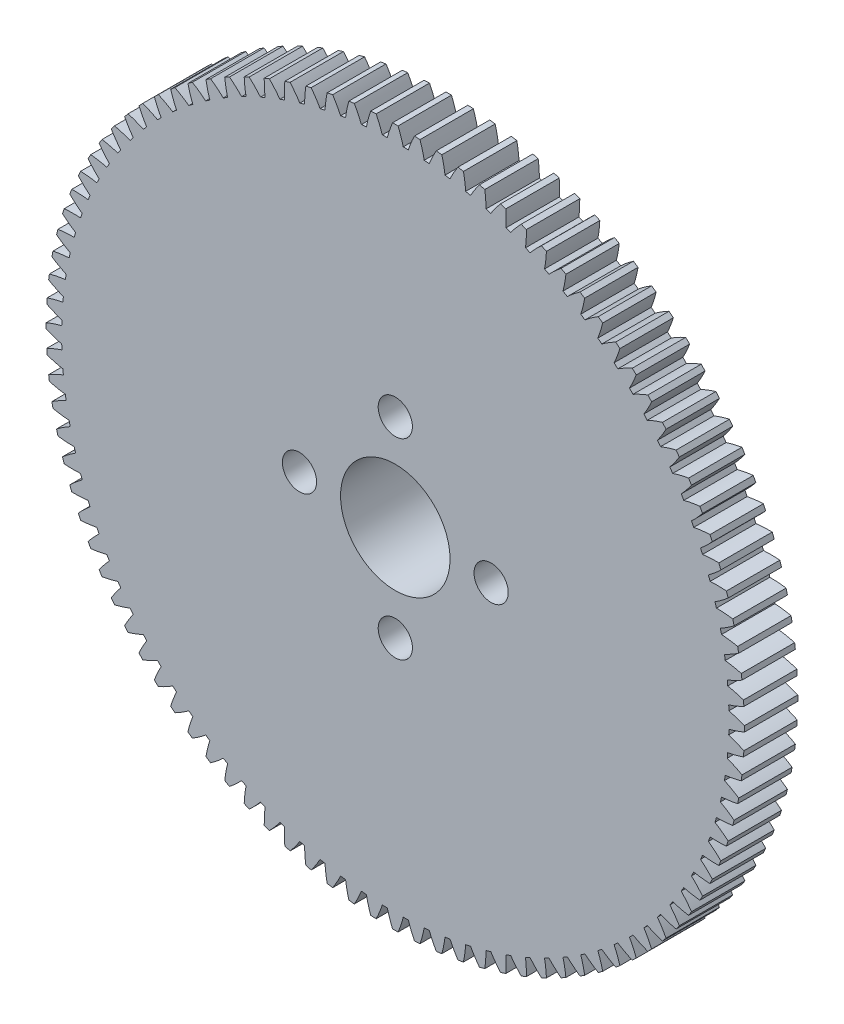
SolidWorks part; units mm, degrees
material "ABS"
ref_plane "Front Plane" through (0, 0, 0) normal (0, 0, 1) x (1, 0, 0)
ref_plane "Top Plane" through (0, 0, 0) normal (0, 1, 0) x (1, 0, 0)
ref_plane "Right Plane" through (0, 0, 0) normal (1, 0, 0) x (0, 0, -1)
ref_plane "Plane1" through (0, 0, 4.1) normal (0, 0, 1) x (1, 0, 0)
sketch "Sketch1" plane through (0, 0, 4.1) normal (0, 0, 1) x (1, 0, 0)
  line L0 (25.4992, -0.2018) -> (25.4992, 0.2018)
  line L1 (25.4616, 1.3997) -> (25.4362, 1.8025)
  line L2 (25.3234, 2.9957) -> (25.2728, 3.3961)
  line L3 (25.0854, 4.5799) -> (25.0097, 4.9763)
  line L4 (24.7483, 6.1459) -> (24.6479, 6.5369)
  line L5 (24.3135, 7.6878) -> (24.1888, 8.0716)
  line L6 (23.7828, 9.1993) -> (23.6343, 9.5745)
  line L7 (23.1583, 10.6744) -> (22.9864, 11.0396)
  line L8 (22.4423, 12.1075) -> (22.2479, 12.4612)
  line L9 (21.6378, 13.4928) -> (21.4216, 13.8335)
  line L10 (20.7479, 14.8248) -> (20.5107, 15.1513)
  line L11 (19.7761, 16.0983) -> (19.5188, 16.4093)
  line L12 (18.7263, 17.3083) -> (18.45, 17.6025)
  line L13 (17.6025, 18.45) -> (17.3083, 18.7263)
  line L14 (16.4093, 19.5188) -> (16.0983, 19.7761)
  line L15 (15.1513, 20.5107) -> (14.8248, 20.7479)
  line L16 (13.8335, 21.4216) -> (13.4928, 21.6378)
  line L17 (12.4612, 22.2479) -> (12.1075, 22.4423)
  line L18 (11.0396, 22.9864) -> (10.6744, 23.1583)
  line L19 (9.5745, 23.6343) -> (9.1993, 23.7828)
  line L20 (8.0716, 24.1888) -> (7.6878, 24.3135)
  line L21 (6.5369, 24.6479) -> (6.1459, 24.7483)
  line L22 (4.9763, 25.0097) -> (4.5799, 25.0854)
  line L23 (3.3961, 25.2728) -> (2.9957, 25.3234)
  line L24 (1.8025, 25.4362) -> (1.3997, 25.4616)
  line L25 (0.2018, 25.4992) -> (-0.2018, 25.4992)
  line L26 (-1.3997, 25.4616) -> (-1.8025, 25.4362)
  line L27 (-2.9957, 25.3234) -> (-3.3961, 25.2728)
  line L28 (-4.5799, 25.0854) -> (-4.9763, 25.0097)
  line L29 (-6.1459, 24.7483) -> (-6.5369, 24.6479)
  line L30 (-7.6878, 24.3135) -> (-8.0716, 24.1888)
  line L31 (-9.1993, 23.7828) -> (-9.5745, 23.6343)
  line L32 (-10.6744, 23.1583) -> (-11.0396, 22.9864)
  line L33 (-12.1075, 22.4423) -> (-12.4612, 22.2479)
  line L34 (-13.4928, 21.6378) -> (-13.8335, 21.4216)
  line L35 (-14.8248, 20.7479) -> (-15.1513, 20.5107)
  line L36 (-16.0983, 19.7761) -> (-16.4093, 19.5188)
  line L37 (-17.3083, 18.7263) -> (-17.6025, 18.45)
  line L38 (-18.45, 17.6025) -> (-18.7263, 17.3083)
  line L39 (-19.5188, 16.4093) -> (-19.7761, 16.0983)
  line L40 (-20.5107, 15.1513) -> (-20.7479, 14.8248)
  line L41 (-21.4216, 13.8335) -> (-21.6378, 13.4928)
  line L42 (-22.2479, 12.4612) -> (-22.4423, 12.1075)
  line L43 (-22.9864, 11.0396) -> (-23.1583, 10.6744)
  line L44 (-23.6343, 9.5745) -> (-23.7828, 9.1993)
  line L45 (-24.1888, 8.0716) -> (-24.3135, 7.6878)
  line L46 (-24.6479, 6.5369) -> (-24.7483, 6.1459)
  line L47 (-25.0097, 4.9763) -> (-25.0854, 4.5799)
  line L48 (-25.2728, 3.3961) -> (-25.3234, 2.9957)
  line L49 (-25.4362, 1.8025) -> (-25.4616, 1.3997)
  line L50 (-25.4992, 0.2018) -> (-25.4992, -0.2018)
  line L51 (-25.4616, -1.3997) -> (-25.4362, -1.8025)
  line L52 (-25.3234, -2.9957) -> (-25.2728, -3.3961)
  line L53 (-25.0854, -4.5799) -> (-25.0097, -4.9763)
  line L54 (-24.7483, -6.1459) -> (-24.6479, -6.5369)
  line L55 (-24.3135, -7.6878) -> (-24.1888, -8.0716)
  line L56 (-23.7828, -9.1993) -> (-23.6343, -9.5745)
  line L57 (-23.1583, -10.6744) -> (-22.9864, -11.0396)
  line L58 (-22.4423, -12.1075) -> (-22.2479, -12.4612)
  line L59 (-21.6378, -13.4928) -> (-21.4216, -13.8335)
  line L60 (-20.7479, -14.8248) -> (-20.5107, -15.1513)
  line L61 (-19.7761, -16.0983) -> (-19.5188, -16.4093)
  line L62 (-18.7263, -17.3083) -> (-18.45, -17.6025)
  line L63 (-17.6025, -18.45) -> (-17.3083, -18.7263)
  line L64 (-16.4093, -19.5188) -> (-16.0983, -19.7761)
  line L65 (-15.1513, -20.5107) -> (-14.8248, -20.7479)
  line L66 (-13.8335, -21.4216) -> (-13.4928, -21.6378)
  line L67 (-12.4612, -22.2479) -> (-12.1075, -22.4423)
  line L68 (-11.0396, -22.9864) -> (-10.6744, -23.1583)
  line L69 (-9.5745, -23.6343) -> (-9.1993, -23.7828)
  line L70 (-8.0716, -24.1888) -> (-7.6878, -24.3135)
  line L71 (-6.5369, -24.6479) -> (-6.1459, -24.7483)
  line L72 (-4.9763, -25.0097) -> (-4.5799, -25.0854)
  line L73 (-3.3961, -25.2728) -> (-2.9957, -25.3234)
  line L74 (-1.8025, -25.4362) -> (-1.3997, -25.4616)
  line L75 (-0.2018, -25.4992) -> (0.2018, -25.4992)
  line L76 (1.3997, -25.4616) -> (1.8025, -25.4362)
  line L77 (2.9957, -25.3234) -> (3.3961, -25.2728)
  line L78 (4.5799, -25.0854) -> (4.9763, -25.0097)
  line L79 (6.1459, -24.7483) -> (6.5369, -24.6479)
  line L80 (7.6878, -24.3135) -> (8.0716, -24.1888)
  line L81 (9.1993, -23.7828) -> (9.5745, -23.6343)
  line L82 (10.6744, -23.1583) -> (11.0396, -22.9864)
  line L83 (12.1075, -22.4423) -> (12.4612, -22.2479)
  line L84 (13.4928, -21.6378) -> (13.8335, -21.4216)
  line L85 (14.8248, -20.7479) -> (15.1513, -20.5107)
  line L86 (16.0983, -19.7761) -> (16.4093, -19.5188)
  line L87 (17.3083, -18.7263) -> (17.6025, -18.45)
  line L88 (18.45, -17.6025) -> (18.7263, -17.3083)
  line L89 (19.5188, -16.4093) -> (19.7761, -16.0983)
  line L90 (20.5107, -15.1513) -> (20.7479, -14.8248)
  line L91 (21.4216, -13.8335) -> (21.6378, -13.4928)
  line L92 (22.2479, -12.4612) -> (22.4423, -12.1075)
  line L93 (22.9864, -11.0396) -> (23.1583, -10.6744)
  line L94 (23.6343, -9.5745) -> (23.7828, -9.1993)
  line L95 (24.1888, -8.0716) -> (24.3135, -7.6878)
  line L96 (24.6479, -6.5369) -> (24.7483, -6.1459)
  line L97 (25.0097, -4.9763) -> (25.0854, -4.5799)
  line L98 (25.2728, -3.3961) -> (25.3234, -2.9957)
  line L99 (25.4362, -1.8025) -> (25.4616, -1.3997)
  arc A0 (24.3565, -0.9497) -> (24.3681, -0.5815) centre (0, 0) ccw
  arc A1 (24.3681, -0.5815) -> (25.4992, -0.2018) centre (22.3084, 7.4288) ccw
  arc A2 (25.4992, 0.2018) -> (24.3681, 0.5815) centre (22.3272, -7.3729) ccw
  arc A3 (24.3681, 0.5815) -> (24.3565, 0.9497) centre (0, 0) ccw
  arc A4 (24.3565, 0.9497) -> (25.4616, 1.3997) centre (21.7979, 8.8149) ccw
  arc A5 (25.4362, 1.8025) -> (24.2835, 2.1104) centre (22.7461, -5.9564) ccw
  arc A6 (24.2835, 2.1104) -> (24.2488, 2.4772) centre (0, 0) ccw
  arc A7 (24.2488, 2.4772) -> (25.3234, 2.9957) centre (21.2014, 10.1662) ccw
  arc A8 (25.2728, 3.3961) -> (24.103, 3.631) centre (23.0752, -4.5164) ccw
  arc A9 (24.103, 3.631) -> (24.0454, 3.9949) centre (0, 0) ccw
  arc A10 (24.0454, 3.9949) -> (25.0854, 4.5799) centre (20.5213, 11.4774) ccw
  arc A11 (25.0097, 4.9763) -> (23.8275, 5.1373) centre (23.3132, -3.0586) ccw
  arc A12 (23.8275, 5.1373) -> (23.7471, 5.4969) centre (0, 0) ccw
  arc A13 (23.7471, 5.4969) -> (24.7483, 6.1459) centre (19.7601, 12.7433) ccw
  arc A14 (24.6479, 6.5369) -> (23.4579, 6.6233) centre (23.4593, -1.5887) ccw
  arc A15 (23.4579, 6.6233) -> (23.3551, 6.9771) centre (0, 0) ccw
  arc A16 (23.3551, 6.9771) -> (24.3135, 7.6878) centre (18.921, 13.9589) ccw
  arc A17 (24.1888, 8.0716) -> (22.9957, 8.0832) centre (23.5128, -0.1125) ccw
  arc A18 (22.9957, 8.0832) -> (22.8709, 8.4298) centre (0, 0) ccw
  arc A19 (22.8709, 8.4298) -> (23.7828, 9.1993) centre (18.0071, 15.1194) ccw
  arc A20 (23.6343, 9.5745) -> (22.4428, 9.5112) centre (23.4734, 1.3641) ccw
  arc A21 (22.4428, 9.5112) -> (22.2965, 9.8493) centre (0, 0) ccw
  arc A22 (22.2965, 9.8493) -> (23.1583, 10.6744) centre (17.0222, 16.2202) ccw
  arc A23 (22.9864, 11.0396) -> (21.8013, 10.9016) centre (23.3415, 2.8353) ccw
  arc A24 (21.8013, 10.9016) -> (21.634, 11.2298) centre (0, 0) ccw
  arc A25 (21.634, 11.2298) -> (22.4423, 12.1075) centre (15.9702, 17.257) ccw
  arc A26 (22.2479, 12.4612) -> (21.0738, 12.249) centre (23.1174, 4.2953) ccw
  arc A27 (21.0738, 12.249) -> (20.8862, 12.5661) centre (0, 0) ccw
  arc A28 (20.8862, 12.5661) -> (21.6378, 13.4928) centre (14.8551, 18.2258) ccw
  arc A29 (21.4216, 13.8335) -> (20.263, 13.548) centre (22.8021, 5.7384) ccw
  arc A30 (20.263, 13.548) -> (20.056, 13.8527) centre (0, 0) ccw
  arc A31 (20.056, 13.8527) -> (20.7479, 14.8248) centre (13.6814, 19.1226) ccw
  arc A32 (20.5107, 15.1513) -> (19.3724, 14.7936) centre (22.3967, 7.1588) ccw
  arc A33 (19.3724, 14.7936) -> (19.1466, 15.0847) centre (0, 0) ccw
  arc A34 (19.1466, 15.0847) -> (19.7761, 16.0983) centre (12.4537, 19.9439) ccw
  arc A35 (19.5188, 16.4093) -> (18.4052, 15.9808) centre (21.903, 8.551) ccw
  arc A36 (18.4052, 15.9808) -> (18.1616, 16.2572) centre (0, 0) ccw
  arc A37 (18.1616, 16.2572) -> (18.7263, 17.3083) centre (11.1768, 20.6865) ccw
  arc A38 (18.45, 17.6025) -> (17.3655, 17.105) centre (21.3229, 9.9094) ccw
  arc A39 (17.3655, 17.105) -> (17.105, 17.3655) centre (0, 0) ccw
  arc A40 (17.105, 17.3655) -> (17.6025, 18.45) centre (9.8558, 21.3475) ccw
  arc A41 (17.3083, 18.7263) -> (16.2572, 18.1616) centre (20.6586, 11.2287) ccw
  arc A42 (16.2572, 18.1616) -> (15.9808, 18.4052) centre (0, 0) ccw
  arc A43 (15.9808, 18.4052) -> (16.4093, 19.5188) centre (8.496, 21.9242) ccw
  arc A44 (16.0983, 19.7761) -> (15.0847, 19.1466) centre (19.9128, 12.5037) ccw
  arc A45 (15.0847, 19.1466) -> (14.7936, 19.3724) centre (0, 0) ccw
  arc A46 (14.7936, 19.3724) -> (15.1513, 20.5107) centre (7.1026, 22.4144) ccw
  arc A47 (14.8248, 20.7479) -> (13.8527, 20.056) centre (19.0884, 13.7294) ccw
  arc A48 (13.8527, 20.056) -> (13.548, 20.263) centre (0, 0) ccw
  arc A49 (13.548, 20.263) -> (13.8335, 21.4216) centre (5.6811, 22.8162) ccw
  arc A50 (13.4928, 21.6378) -> (12.5661, 20.8862) centre (18.1886, 14.9009) ccw
  arc A51 (12.5661, 20.8862) -> (12.249, 21.0738) centre (0, 0) ccw
  arc A52 (12.249, 21.0738) -> (12.4612, 22.2479) centre (4.2373, 23.1279) ccw
  arc A53 (12.1075, 22.4423) -> (11.2298, 21.634) centre (17.2171, 16.0136) ccw
  arc A54 (11.2298, 21.634) -> (10.9016, 21.8013) centre (0, 0) ccw
  arc A55 (10.9016, 21.8013) -> (11.0396, 22.9864) centre (2.7767, 23.3483) ccw
  arc A56 (10.6744, 23.1583) -> (9.8493, 22.2965) centre (16.1776, 17.063) ccw
  arc A57 (9.8493, 22.2965) -> (9.5112, 22.4428) centre (0, 0) ccw
  arc A58 (9.5112, 22.4428) -> (9.5745, 23.6343) centre (1.3052, 23.4766) ccw
  arc A59 (9.1993, 23.7828) -> (8.4298, 22.8709) centre (15.0743, 18.0452) ccw
  arc A60 (8.4298, 22.8709) -> (8.0832, 22.9957) centre (0, 0) ccw
  arc A61 (8.0832, 22.9957) -> (8.0716, 24.1888) centre (-0.1715, 23.5122) ccw
  arc A62 (7.6878, 24.3135) -> (6.9771, 23.3551) centre (13.9115, 18.9561) ccw
  arc A63 (6.9771, 23.3551) -> (6.6233, 23.4579) centre (0, 0) ccw
  arc A64 (6.6233, 23.4579) -> (6.5369, 24.6479) centre (-1.6475, 23.455) ccw
  arc A65 (6.1459, 24.7483) -> (5.4969, 23.7471) centre (12.6938, 19.7922) ccw
  arc A66 (5.4969, 23.7471) -> (5.1373, 23.8275) centre (0, 0) ccw
  arc A67 (5.1373, 23.8275) -> (4.9763, 25.0097) centre (-3.117, 23.3053) ccw
  arc A68 (4.5799, 25.0854) -> (3.9949, 24.0454) centre (11.426, 20.5502) ccw
  arc A69 (3.9949, 24.0454) -> (3.631, 24.103) centre (0, 0) ccw
  arc A70 (3.631, 24.103) -> (3.3961, 25.2728) centre (-4.5742, 23.0636) ccw
  arc A71 (2.9957, 25.3234) -> (2.4772, 24.2488) centre (10.1131, 21.2271) ccw
  arc A72 (2.4772, 24.2488) -> (2.1104, 24.2835) centre (0, 0) ccw
  arc A73 (2.1104, 24.2835) -> (1.8025, 25.4362) centre (-6.0134, 22.7309) ccw
  arc A74 (1.3997, 25.4616) -> (0.9497, 24.3565) centre (8.7603, 21.8202) ccw
  arc A75 (0.9497, 24.3565) -> (0.5815, 24.3681) centre (0, 0) ccw
  arc A76 (0.5815, 24.3681) -> (0.2018, 25.4992) centre (-7.4288, 22.3084) ccw
  arc A77 (-0.2018, 25.4992) -> (-0.5815, 24.3681) centre (7.3729, 22.3272) ccw
  arc A78 (-0.5815, 24.3681) -> (-0.9497, 24.3565) centre (0, 0) ccw
  arc A79 (-0.9497, 24.3565) -> (-1.3997, 25.4616) centre (-8.8149, 21.7979) ccw
  arc A80 (-1.8025, 25.4362) -> (-2.1104, 24.2835) centre (5.9564, 22.7461) ccw
  arc A81 (-2.1104, 24.2835) -> (-2.4772, 24.2488) centre (0, 0) ccw
  arc A82 (-2.4772, 24.2488) -> (-2.9957, 25.3234) centre (-10.1662, 21.2014) ccw
  arc A83 (-3.3961, 25.2728) -> (-3.631, 24.103) centre (4.5164, 23.0752) ccw
  arc A84 (-3.631, 24.103) -> (-3.9949, 24.0454) centre (0, 0) ccw
  arc A85 (-3.9949, 24.0454) -> (-4.5799, 25.0854) centre (-11.4774, 20.5213) ccw
  arc A86 (-4.9763, 25.0097) -> (-5.1373, 23.8275) centre (3.0586, 23.3132) ccw
  arc A87 (-5.1373, 23.8275) -> (-5.4969, 23.7471) centre (0, 0) ccw
  arc A88 (-5.4969, 23.7471) -> (-6.1459, 24.7483) centre (-12.7433, 19.7601) ccw
  arc A89 (-6.5369, 24.6479) -> (-6.6233, 23.4579) centre (1.5887, 23.4593) ccw
  arc A90 (-6.6233, 23.4579) -> (-6.9771, 23.3551) centre (0, 0) ccw
  arc A91 (-6.9771, 23.3551) -> (-7.6878, 24.3135) centre (-13.9589, 18.921) ccw
  arc A92 (-8.0716, 24.1888) -> (-8.0832, 22.9957) centre (0.1125, 23.5128) ccw
  arc A93 (-8.0832, 22.9957) -> (-8.4298, 22.8709) centre (0, 0) ccw
  arc A94 (-8.4298, 22.8709) -> (-9.1993, 23.7828) centre (-15.1194, 18.0071) ccw
  arc A95 (-9.5745, 23.6343) -> (-9.5112, 22.4428) centre (-1.3641, 23.4734) ccw
  arc A96 (-9.5112, 22.4428) -> (-9.8493, 22.2965) centre (0, 0) ccw
  arc A97 (-9.8493, 22.2965) -> (-10.6744, 23.1583) centre (-16.2202, 17.0222) ccw
  arc A98 (-11.0396, 22.9864) -> (-10.9016, 21.8013) centre (-2.8353, 23.3415) ccw
  arc A99 (-10.9016, 21.8013) -> (-11.2298, 21.634) centre (0, 0) ccw
  arc A100 (-11.2298, 21.634) -> (-12.1075, 22.4423) centre (-17.257, 15.9702) ccw
  arc A101 (-12.4612, 22.2479) -> (-12.249, 21.0738) centre (-4.2953, 23.1174) ccw
  arc A102 (-12.249, 21.0738) -> (-12.5661, 20.8862) centre (0, 0) ccw
  arc A103 (-12.5661, 20.8862) -> (-13.4928, 21.6378) centre (-18.2258, 14.8551) ccw
  arc A104 (-13.8335, 21.4216) -> (-13.548, 20.263) centre (-5.7384, 22.8021) ccw
  arc A105 (-13.548, 20.263) -> (-13.8527, 20.056) centre (0, 0) ccw
  arc A106 (-13.8527, 20.056) -> (-14.8248, 20.7479) centre (-19.1226, 13.6814) ccw
  arc A107 (-15.1513, 20.5107) -> (-14.7936, 19.3724) centre (-7.1588, 22.3967) ccw
  arc A108 (-14.7936, 19.3724) -> (-15.0847, 19.1466) centre (0, 0) ccw
  arc A109 (-15.0847, 19.1466) -> (-16.0983, 19.7761) centre (-19.9439, 12.4537) ccw
  arc A110 (-16.4093, 19.5188) -> (-15.9808, 18.4052) centre (-8.551, 21.903) ccw
  arc A111 (-15.9808, 18.4052) -> (-16.2572, 18.1616) centre (0, 0) ccw
  arc A112 (-16.2572, 18.1616) -> (-17.3083, 18.7263) centre (-20.6865, 11.1768) ccw
  arc A113 (-17.6025, 18.45) -> (-17.105, 17.3655) centre (-9.9094, 21.3229) ccw
  arc A114 (-17.105, 17.3655) -> (-17.3655, 17.105) centre (0, 0) ccw
  arc A115 (-17.3655, 17.105) -> (-18.45, 17.6025) centre (-21.3475, 9.8558) ccw
  arc A116 (-18.7263, 17.3083) -> (-18.1616, 16.2572) centre (-11.2287, 20.6586) ccw
  arc A117 (-18.1616, 16.2572) -> (-18.4052, 15.9808) centre (0, 0) ccw
  arc A118 (-18.4052, 15.9808) -> (-19.5188, 16.4093) centre (-21.9242, 8.496) ccw
  arc A119 (-19.7761, 16.0983) -> (-19.1466, 15.0847) centre (-12.5037, 19.9128) ccw
  arc A120 (-19.1466, 15.0847) -> (-19.3724, 14.7936) centre (0, 0) ccw
  arc A121 (-19.3724, 14.7936) -> (-20.5107, 15.1513) centre (-22.4144, 7.1026) ccw
  arc A122 (-20.7479, 14.8248) -> (-20.056, 13.8527) centre (-13.7294, 19.0884) ccw
  arc A123 (-20.056, 13.8527) -> (-20.263, 13.548) centre (0, 0) ccw
  arc A124 (-20.263, 13.548) -> (-21.4216, 13.8335) centre (-22.8162, 5.6811) ccw
  arc A125 (-21.6378, 13.4928) -> (-20.8862, 12.5661) centre (-14.9009, 18.1886) ccw
  arc A126 (-20.8862, 12.5661) -> (-21.0738, 12.249) centre (0, 0) ccw
  arc A127 (-21.0738, 12.249) -> (-22.2479, 12.4612) centre (-23.1279, 4.2373) ccw
  arc A128 (-22.4423, 12.1075) -> (-21.634, 11.2298) centre (-16.0136, 17.2171) ccw
  arc A129 (-21.634, 11.2298) -> (-21.8013, 10.9016) centre (0, 0) ccw
  arc A130 (-21.8013, 10.9016) -> (-22.9864, 11.0396) centre (-23.3483, 2.7767) ccw
  arc A131 (-23.1583, 10.6744) -> (-22.2965, 9.8493) centre (-17.063, 16.1776) ccw
  arc A132 (-22.2965, 9.8493) -> (-22.4428, 9.5112) centre (0, 0) ccw
  arc A133 (-22.4428, 9.5112) -> (-23.6343, 9.5745) centre (-23.4766, 1.3052) ccw
  arc A134 (-23.7828, 9.1993) -> (-22.8709, 8.4298) centre (-18.0452, 15.0743) ccw
  arc A135 (-22.8709, 8.4298) -> (-22.9957, 8.0832) centre (0, 0) ccw
  arc A136 (-22.9957, 8.0832) -> (-24.1888, 8.0716) centre (-23.5122, -0.1715) ccw
  arc A137 (-24.3135, 7.6878) -> (-23.3551, 6.9771) centre (-18.9561, 13.9115) ccw
  arc A138 (-23.3551, 6.9771) -> (-23.4579, 6.6233) centre (0, 0) ccw
  arc A139 (-23.4579, 6.6233) -> (-24.6479, 6.5369) centre (-23.455, -1.6475) ccw
  arc A140 (-24.7483, 6.1459) -> (-23.7471, 5.4969) centre (-19.7922, 12.6938) ccw
  arc A141 (-23.7471, 5.4969) -> (-23.8275, 5.1373) centre (0, 0) ccw
  arc A142 (-23.8275, 5.1373) -> (-25.0097, 4.9763) centre (-23.3053, -3.117) ccw
  arc A143 (-25.0854, 4.5799) -> (-24.0454, 3.9949) centre (-20.5502, 11.426) ccw
  arc A144 (-24.0454, 3.9949) -> (-24.103, 3.631) centre (0, 0) ccw
  arc A145 (-24.103, 3.631) -> (-25.2728, 3.3961) centre (-23.0636, -4.5742) ccw
  arc A146 (-25.3234, 2.9957) -> (-24.2488, 2.4772) centre (-21.2271, 10.1131) ccw
  arc A147 (-24.2488, 2.4772) -> (-24.2835, 2.1104) centre (0, 0) ccw
  arc A148 (-24.2835, 2.1104) -> (-25.4362, 1.8025) centre (-22.7309, -6.0134) ccw
  arc A149 (-25.4616, 1.3997) -> (-24.3565, 0.9497) centre (-21.8202, 8.7603) ccw
  arc A150 (-24.3565, 0.9497) -> (-24.3681, 0.5815) centre (0, 0) ccw
  arc A151 (-24.3681, 0.5815) -> (-25.4992, 0.2018) centre (-22.3084, -7.4288) ccw
  arc A152 (-25.4992, -0.2018) -> (-24.3681, -0.5815) centre (-22.3272, 7.3729) ccw
  arc A153 (-24.3681, -0.5815) -> (-24.3565, -0.9497) centre (0, 0) ccw
  arc A154 (-24.3565, -0.9497) -> (-25.4616, -1.3997) centre (-21.7979, -8.8149) ccw
  arc A155 (-25.4362, -1.8025) -> (-24.2835, -2.1104) centre (-22.7461, 5.9564) ccw
  arc A156 (-24.2835, -2.1104) -> (-24.2488, -2.4772) centre (0, 0) ccw
  arc A157 (-24.2488, -2.4772) -> (-25.3234, -2.9957) centre (-21.2014, -10.1662) ccw
  arc A158 (-25.2728, -3.3961) -> (-24.103, -3.631) centre (-23.0752, 4.5164) ccw
  arc A159 (-24.103, -3.631) -> (-24.0454, -3.9949) centre (0, 0) ccw
  arc A160 (-24.0454, -3.9949) -> (-25.0854, -4.5799) centre (-20.5213, -11.4774) ccw
  arc A161 (-25.0097, -4.9763) -> (-23.8275, -5.1373) centre (-23.3132, 3.0586) ccw
  arc A162 (-23.8275, -5.1373) -> (-23.7471, -5.4969) centre (0, 0) ccw
  arc A163 (-23.7471, -5.4969) -> (-24.7483, -6.1459) centre (-19.7601, -12.7433) ccw
  arc A164 (-24.6479, -6.5369) -> (-23.4579, -6.6233) centre (-23.4593, 1.5887) ccw
  arc A165 (-23.4579, -6.6233) -> (-23.3551, -6.9771) centre (0, 0) ccw
  arc A166 (-23.3551, -6.9771) -> (-24.3135, -7.6878) centre (-18.921, -13.9589) ccw
  arc A167 (-24.1888, -8.0716) -> (-22.9957, -8.0832) centre (-23.5128, 0.1125) ccw
  arc A168 (-22.9957, -8.0832) -> (-22.8709, -8.4298) centre (0, 0) ccw
  arc A169 (-22.8709, -8.4298) -> (-23.7828, -9.1993) centre (-18.0071, -15.1194) ccw
  arc A170 (-23.6343, -9.5745) -> (-22.4428, -9.5112) centre (-23.4734, -1.3641) ccw
  arc A171 (-22.4428, -9.5112) -> (-22.2965, -9.8493) centre (0, 0) ccw
  arc A172 (-22.2965, -9.8493) -> (-23.1583, -10.6744) centre (-17.0222, -16.2202) ccw
  arc A173 (-22.9864, -11.0396) -> (-21.8013, -10.9016) centre (-23.3415, -2.8353) ccw
  arc A174 (-21.8013, -10.9016) -> (-21.634, -11.2298) centre (0, 0) ccw
  arc A175 (-21.634, -11.2298) -> (-22.4423, -12.1075) centre (-15.9702, -17.257) ccw
  arc A176 (-22.2479, -12.4612) -> (-21.0738, -12.249) centre (-23.1174, -4.2953) ccw
  arc A177 (-21.0738, -12.249) -> (-20.8862, -12.5661) centre (0, 0) ccw
  arc A178 (-20.8862, -12.5661) -> (-21.6378, -13.4928) centre (-14.8551, -18.2258) ccw
  arc A179 (-21.4216, -13.8335) -> (-20.263, -13.548) centre (-22.8021, -5.7384) ccw
  arc A180 (-20.263, -13.548) -> (-20.056, -13.8527) centre (0, 0) ccw
  arc A181 (-20.056, -13.8527) -> (-20.7479, -14.8248) centre (-13.6814, -19.1226) ccw
  arc A182 (-20.5107, -15.1513) -> (-19.3724, -14.7936) centre (-22.3967, -7.1588) ccw
  arc A183 (-19.3724, -14.7936) -> (-19.1466, -15.0847) centre (0, 0) ccw
  arc A184 (-19.1466, -15.0847) -> (-19.7761, -16.0983) centre (-12.4537, -19.9439) ccw
  arc A185 (-19.5188, -16.4093) -> (-18.4052, -15.9808) centre (-21.903, -8.551) ccw
  arc A186 (-18.4052, -15.9808) -> (-18.1616, -16.2572) centre (0, 0) ccw
  arc A187 (-18.1616, -16.2572) -> (-18.7263, -17.3083) centre (-11.1768, -20.6865) ccw
  arc A188 (-18.45, -17.6025) -> (-17.3655, -17.105) centre (-21.3229, -9.9094) ccw
  arc A189 (-17.3655, -17.105) -> (-17.105, -17.3655) centre (0, 0) ccw
  arc A190 (-17.105, -17.3655) -> (-17.6025, -18.45) centre (-9.8558, -21.3475) ccw
  arc A191 (-17.3083, -18.7263) -> (-16.2572, -18.1616) centre (-20.6586, -11.2287) ccw
  arc A192 (-16.2572, -18.1616) -> (-15.9808, -18.4052) centre (0, 0) ccw
  arc A193 (-15.9808, -18.4052) -> (-16.4093, -19.5188) centre (-8.496, -21.9242) ccw
  arc A194 (-16.0983, -19.7761) -> (-15.0847, -19.1466) centre (-19.9128, -12.5037) ccw
  arc A195 (-15.0847, -19.1466) -> (-14.7936, -19.3724) centre (0, 0) ccw
  arc A196 (-14.7936, -19.3724) -> (-15.1513, -20.5107) centre (-7.1026, -22.4144) ccw
  arc A197 (-14.8248, -20.7479) -> (-13.8527, -20.056) centre (-19.0884, -13.7294) ccw
  arc A198 (-13.8527, -20.056) -> (-13.548, -20.263) centre (0, 0) ccw
  arc A199 (-13.548, -20.263) -> (-13.8335, -21.4216) centre (-5.6811, -22.8162) ccw
  arc A200 (-13.4928, -21.6378) -> (-12.5661, -20.8862) centre (-18.1886, -14.9009) ccw
  arc A201 (-12.5661, -20.8862) -> (-12.249, -21.0738) centre (0, 0) ccw
  arc A202 (-12.249, -21.0738) -> (-12.4612, -22.2479) centre (-4.2373, -23.1279) ccw
  arc A203 (-12.1075, -22.4423) -> (-11.2298, -21.634) centre (-17.2171, -16.0136) ccw
  arc A204 (-11.2298, -21.634) -> (-10.9016, -21.8013) centre (0, 0) ccw
  arc A205 (-10.9016, -21.8013) -> (-11.0396, -22.9864) centre (-2.7767, -23.3483) ccw
  arc A206 (-10.6744, -23.1583) -> (-9.8493, -22.2965) centre (-16.1776, -17.063) ccw
  arc A207 (-9.8493, -22.2965) -> (-9.5112, -22.4428) centre (0, 0) ccw
  arc A208 (-9.5112, -22.4428) -> (-9.5745, -23.6343) centre (-1.3052, -23.4766) ccw
  arc A209 (-9.1993, -23.7828) -> (-8.4298, -22.8709) centre (-15.0743, -18.0452) ccw
  arc A210 (-8.4298, -22.8709) -> (-8.0832, -22.9957) centre (0, 0) ccw
  arc A211 (-8.0832, -22.9957) -> (-8.0716, -24.1888) centre (0.1715, -23.5122) ccw
  arc A212 (-7.6878, -24.3135) -> (-6.9771, -23.3551) centre (-13.9115, -18.9561) ccw
  arc A213 (-6.9771, -23.3551) -> (-6.6233, -23.4579) centre (0, 0) ccw
  arc A214 (-6.6233, -23.4579) -> (-6.5369, -24.6479) centre (1.6475, -23.455) ccw
  arc A215 (-6.1459, -24.7483) -> (-5.4969, -23.7471) centre (-12.6938, -19.7922) ccw
  arc A216 (-5.4969, -23.7471) -> (-5.1373, -23.8275) centre (0, 0) ccw
  arc A217 (-5.1373, -23.8275) -> (-4.9763, -25.0097) centre (3.117, -23.3053) ccw
  arc A218 (-4.5799, -25.0854) -> (-3.9949, -24.0454) centre (-11.426, -20.5502) ccw
  arc A219 (-3.9949, -24.0454) -> (-3.631, -24.103) centre (0, 0) ccw
  arc A220 (-3.631, -24.103) -> (-3.3961, -25.2728) centre (4.5742, -23.0636) ccw
  arc A221 (-2.9957, -25.3234) -> (-2.4772, -24.2488) centre (-10.1131, -21.2271) ccw
  arc A222 (-2.4772, -24.2488) -> (-2.1104, -24.2835) centre (0, 0) ccw
  arc A223 (-2.1104, -24.2835) -> (-1.8025, -25.4362) centre (6.0134, -22.7309) ccw
  arc A224 (-1.3997, -25.4616) -> (-0.9497, -24.3565) centre (-8.7603, -21.8202) ccw
  arc A225 (-0.9497, -24.3565) -> (-0.5815, -24.3681) centre (0, 0) ccw
  arc A226 (-0.5815, -24.3681) -> (-0.2018, -25.4992) centre (7.4288, -22.3084) ccw
  arc A227 (0.2018, -25.4992) -> (0.5815, -24.3681) centre (-7.3729, -22.3272) ccw
  arc A228 (0.5815, -24.3681) -> (0.9497, -24.3565) centre (0, 0) ccw
  arc A229 (0.9497, -24.3565) -> (1.3997, -25.4616) centre (8.8149, -21.7979) ccw
  arc A230 (1.8025, -25.4362) -> (2.1104, -24.2835) centre (-5.9564, -22.7461) ccw
  arc A231 (2.1104, -24.2835) -> (2.4772, -24.2488) centre (0, 0) ccw
  arc A232 (2.4772, -24.2488) -> (2.9957, -25.3234) centre (10.1662, -21.2014) ccw
  arc A233 (3.3961, -25.2728) -> (3.631, -24.103) centre (-4.5164, -23.0752) ccw
  arc A234 (3.631, -24.103) -> (3.9949, -24.0454) centre (0, 0) ccw
  arc A235 (3.9949, -24.0454) -> (4.5799, -25.0854) centre (11.4774, -20.5213) ccw
  arc A236 (4.9763, -25.0097) -> (5.1373, -23.8275) centre (-3.0586, -23.3132) ccw
  arc A237 (5.1373, -23.8275) -> (5.4969, -23.7471) centre (0, 0) ccw
  arc A238 (5.4969, -23.7471) -> (6.1459, -24.7483) centre (12.7433, -19.7601) ccw
  arc A239 (6.5369, -24.6479) -> (6.6233, -23.4579) centre (-1.5887, -23.4593) ccw
  arc A240 (6.6233, -23.4579) -> (6.9771, -23.3551) centre (0, 0) ccw
  arc A241 (6.9771, -23.3551) -> (7.6878, -24.3135) centre (13.9589, -18.921) ccw
  arc A242 (8.0716, -24.1888) -> (8.0832, -22.9957) centre (-0.1125, -23.5128) ccw
  arc A243 (8.0832, -22.9957) -> (8.4298, -22.8709) centre (0, 0) ccw
  arc A244 (8.4298, -22.8709) -> (9.1993, -23.7828) centre (15.1194, -18.0071) ccw
  arc A245 (9.5745, -23.6343) -> (9.5112, -22.4428) centre (1.3641, -23.4734) ccw
  arc A246 (9.5112, -22.4428) -> (9.8493, -22.2965) centre (0, 0) ccw
  arc A247 (9.8493, -22.2965) -> (10.6744, -23.1583) centre (16.2202, -17.0222) ccw
  arc A248 (11.0396, -22.9864) -> (10.9016, -21.8013) centre (2.8353, -23.3415) ccw
  arc A249 (10.9016, -21.8013) -> (11.2298, -21.634) centre (0, 0) ccw
  arc A250 (11.2298, -21.634) -> (12.1075, -22.4423) centre (17.257, -15.9702) ccw
  arc A251 (12.4612, -22.2479) -> (12.249, -21.0738) centre (4.2953, -23.1174) ccw
  arc A252 (12.249, -21.0738) -> (12.5661, -20.8862) centre (0, 0) ccw
  arc A253 (12.5661, -20.8862) -> (13.4928, -21.6378) centre (18.2258, -14.8551) ccw
  arc A254 (13.8335, -21.4216) -> (13.548, -20.263) centre (5.7384, -22.8021) ccw
  arc A255 (13.548, -20.263) -> (13.8527, -20.056) centre (0, 0) ccw
  arc A256 (13.8527, -20.056) -> (14.8248, -20.7479) centre (19.1226, -13.6814) ccw
  arc A257 (15.1513, -20.5107) -> (14.7936, -19.3724) centre (7.1588, -22.3967) ccw
  arc A258 (14.7936, -19.3724) -> (15.0847, -19.1466) centre (0, 0) ccw
  arc A259 (15.0847, -19.1466) -> (16.0983, -19.7761) centre (19.9439, -12.4537) ccw
  arc A260 (16.4093, -19.5188) -> (15.9808, -18.4052) centre (8.551, -21.903) ccw
  arc A261 (15.9808, -18.4052) -> (16.2572, -18.1616) centre (0, 0) ccw
  arc A262 (16.2572, -18.1616) -> (17.3083, -18.7263) centre (20.6865, -11.1768) ccw
  arc A263 (17.6025, -18.45) -> (17.105, -17.3655) centre (9.9094, -21.3229) ccw
  arc A264 (17.105, -17.3655) -> (17.3655, -17.105) centre (0, 0) ccw
  arc A265 (17.3655, -17.105) -> (18.45, -17.6025) centre (21.3475, -9.8558) ccw
  arc A266 (18.7263, -17.3083) -> (18.1616, -16.2572) centre (11.2287, -20.6586) ccw
  arc A267 (18.1616, -16.2572) -> (18.4052, -15.9808) centre (0, 0) ccw
  arc A268 (18.4052, -15.9808) -> (19.5188, -16.4093) centre (21.9242, -8.496) ccw
  arc A269 (19.7761, -16.0983) -> (19.1466, -15.0847) centre (12.5037, -19.9128) ccw
  arc A270 (19.1466, -15.0847) -> (19.3724, -14.7936) centre (0, 0) ccw
  arc A271 (19.3724, -14.7936) -> (20.5107, -15.1513) centre (22.4144, -7.1026) ccw
  arc A272 (20.7479, -14.8248) -> (20.056, -13.8527) centre (13.7294, -19.0884) ccw
  arc A273 (20.056, -13.8527) -> (20.263, -13.548) centre (0, 0) ccw
  arc A274 (20.263, -13.548) -> (21.4216, -13.8335) centre (22.8162, -5.6811) ccw
  arc A275 (21.6378, -13.4928) -> (20.8862, -12.5661) centre (14.9009, -18.1886) ccw
  arc A276 (20.8862, -12.5661) -> (21.0738, -12.249) centre (0, 0) ccw
  arc A277 (21.0738, -12.249) -> (22.2479, -12.4612) centre (23.1279, -4.2373) ccw
  arc A278 (22.4423, -12.1075) -> (21.634, -11.2298) centre (16.0136, -17.2171) ccw
  arc A279 (21.634, -11.2298) -> (21.8013, -10.9016) centre (0, 0) ccw
  arc A280 (21.8013, -10.9016) -> (22.9864, -11.0396) centre (23.3483, -2.7767) ccw
  arc A281 (23.1583, -10.6744) -> (22.2965, -9.8493) centre (17.063, -16.1776) ccw
  arc A282 (22.2965, -9.8493) -> (22.4428, -9.5112) centre (0, 0) ccw
  arc A283 (22.4428, -9.5112) -> (23.6343, -9.5745) centre (23.4766, -1.3052) ccw
  arc A284 (23.7828, -9.1993) -> (22.8709, -8.4298) centre (18.0452, -15.0743) ccw
  arc A285 (22.8709, -8.4298) -> (22.9957, -8.0832) centre (0, 0) ccw
  arc A286 (22.9957, -8.0832) -> (24.1888, -8.0716) centre (23.5122, 0.1715) ccw
  arc A287 (24.3135, -7.6878) -> (23.3551, -6.9771) centre (18.9561, -13.9115) ccw
  arc A288 (23.3551, -6.9771) -> (23.4579, -6.6233) centre (0, 0) ccw
  arc A289 (23.4579, -6.6233) -> (24.6479, -6.5369) centre (23.455, 1.6475) ccw
  arc A290 (24.7483, -6.1459) -> (23.7471, -5.4969) centre (19.7922, -12.6938) ccw
  arc A291 (23.7471, -5.4969) -> (23.8275, -5.1373) centre (0, 0) ccw
  arc A292 (23.8275, -5.1373) -> (25.0097, -4.9763) centre (23.3053, 3.117) ccw
  arc A293 (25.0854, -4.5799) -> (24.0454, -3.9949) centre (20.5502, -11.426) ccw
  arc A294 (24.0454, -3.9949) -> (24.103, -3.631) centre (0, 0) ccw
  arc A295 (24.103, -3.631) -> (25.2728, -3.3961) centre (23.0636, 4.5742) ccw
  arc A296 (25.3234, -2.9957) -> (24.2488, -2.4772) centre (21.2271, -10.1131) ccw
  arc A297 (24.2488, -2.4772) -> (24.2835, -2.1104) centre (0, 0) ccw
  arc A298 (24.2835, -2.1104) -> (25.4362, -1.8025) centre (22.7309, 6.0134) ccw
  arc A299 (25.4616, -1.3997) -> (24.3565, -0.9497) centre (21.8202, -8.7603) ccw
extrude "Boss-Extrude1" add sketch "Sketch1" against normal blind 3.9
sketch "Sketch3" plane through (0, 0, 0.2) normal (0, 0, -1) x (-1, 0, 0)
  circle A0 centre (0, 0) radius 10
  dimension "D1" = 20
extrude "Boss-Extrude2" add sketch "Sketch3" along normal blind 4
sketch "Sketch2" plane through (0, 0, 4.1) normal (0, 0, 1) x (1, 0, 0)
  circle A0 centre (0, 0) radius 4
  circle A1 centre (0, 7) radius 1.25
  circle A2 centre (7, 0) radius 1.25
  circle A3 centre (0, -7) radius 1.25
  circle A4 centre (-7, 0) radius 1.25
  point P14 (0, 0)
  dimension "D1" = 8
  dimension "D2" = 2.5
  dimension "D3" = 7
  dimension "D4" = 4
extrude "Cut-Extrude1" cut sketch "Sketch2" against normal through all
